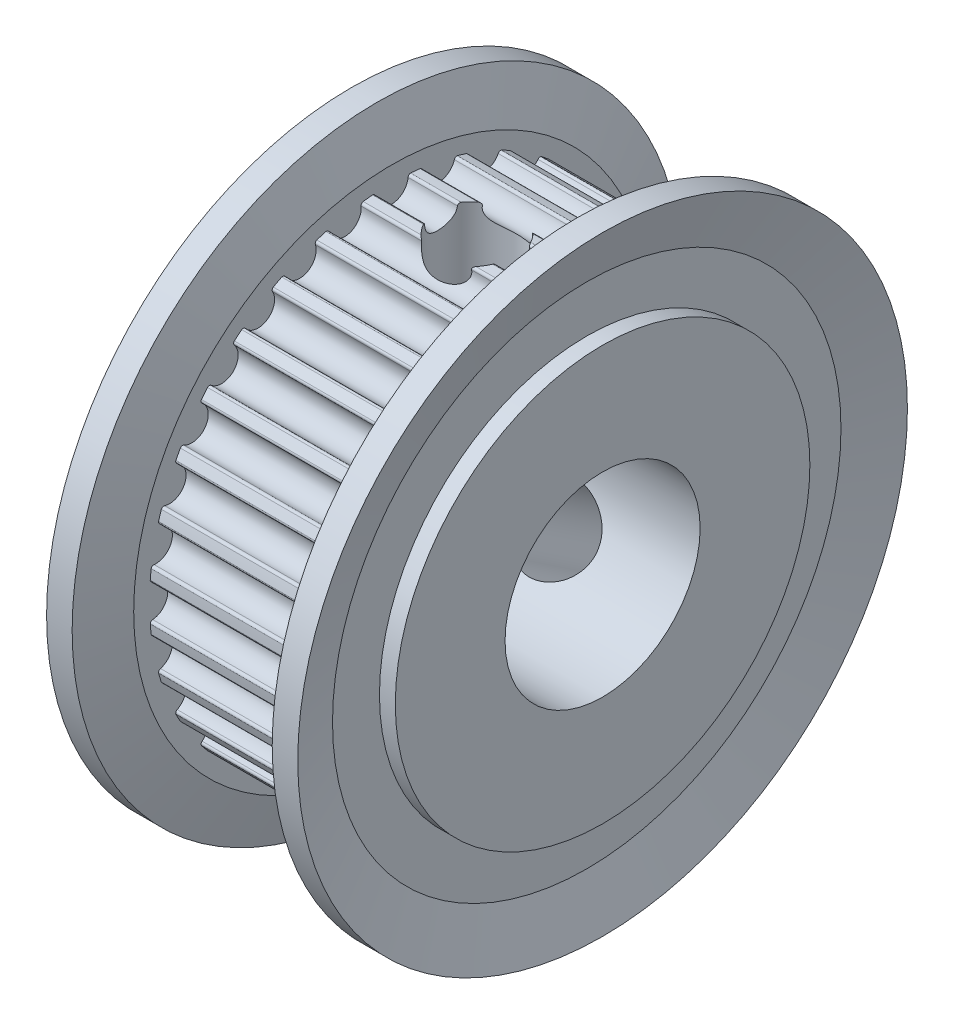
SolidWorks part; units mm, degrees
ref_plane "Front Plane" through (0, 0, 0) normal (0, 0, 1) x (1, 0, 0)
ref_plane "Top Plane" through (0, 0, 0) normal (0, 1, 0) x (1, 0, 0)
ref_plane "Right Plane" through (0, 0, 0) normal (1, 0, 0) x (0, 0, -1)
ref_plane "Plane1" through (0, 0, 0) normal (0, 0, 1) x (1, 0, 0)
sketch "Sketch1" plane through (0, 0, 0) normal (0, 0, 1) x (1, 0, 0)
  line L0 (-5.15, 0) -> (-5.15, 8.5)
  line L1 (-5.15, 8.5) -> (-3.5, 8.5)
  line L2 (-3.5, 8.5) -> (-3.5, 9.93)
  line L3 (-3.5, 9.93) -> (3.5, 9.93)
  line L4 (3.5, 9.93) -> (3.5, 8.5)
  line L5 (3.5, 8.5) -> (5.15, 8.5)
  line L6 (5.15, 8.5) -> (5.15, 0)
  line L7 (5.15, 0) -> (-5.15, 0)
  line L8 (5.15, 0) -> (-5.15, 0) construction
revolve "Revolve1" add sketch "Sketch1" angle 360 about L8
ref_plane "Plane2" through (0, 0, 0) normal (1, 0, 0) x (0, 0, -1)
sketch "Sketch2" plane through (0, 0, 0) normal (1, 0, 0) x (0, 0, -1)
  line L0 (-0.9509, 10.1405) -> (-0.9273, 9.8885)
  line L1 (-0.9273, 9.8885) -> (-0.793, 9.8993)
  line L2 (0.793, 9.8993) -> (0.9273, 9.8885)
  line L3 (0.9273, 9.8885) -> (0.9509, 10.1405)
  arc A0 (-0.793, 9.8993) -> (-0.6724, 9.7974) centre (-0.784, 9.7876) cw
  arc A1 (-0.6724, 9.7974) -> (0.6724, 9.7974) centre (0, 9.856) ccw
  arc A2 (0.6724, 9.7974) -> (0.793, 9.8993) centre (0.784, 9.7876) cw
  arc A3 (0.9509, 10.1405) -> (-0.9509, 10.1405) centre (0, 0) ccw
extrude "Cut-Extrude1" cut sketch "Sketch2" against normal blind 3.5 and the other way blind 3.5
ref_plane "Plane3" through (0, 0, 0) normal (1, 0, 0) x (0, 0, -1)
sketch "Sketch3" plane through (0, 0, 0) normal (1, 0, 0) x (0, 0, -1)
  line L0 (-2.911, 9.7602) -> (-2.8386, 9.5176)
  line L1 (-2.8386, 9.5176) -> (-2.709, 9.5544)
  line L2 (-1.1535, 9.8638) -> (-1.0197, 9.8794)
  line L3 (-1.0197, 9.8794) -> (-1.0457, 10.1312)
  arc A0 (-2.709, 9.5544) -> (-2.5709, 9.4779) centre (-2.6784, 9.4466) cw
  arc A1 (-2.5709, 9.4779) -> (-1.2518, 9.7403) centre (-1.9228, 9.6666) ccw
  arc A2 (-1.2518, 9.7403) -> (-1.1535, 9.8638) centre (-1.1405, 9.7525) cw
  arc A3 (-1.0457, 10.1312) -> (-2.911, 9.7602) centre (0, 0) ccw
extrude "Cut-Extrude2" cut sketch "Sketch3" against normal blind 3.5 and the other way blind 3.5
ref_plane "Plane4" through (0, 0, 0) normal (1, 0, 0) x (0, 0, -1)
sketch "Sketch4" plane through (0, 0, 0) normal (1, 0, 0) x (0, 0, -1)
  line L0 (-4.7591, 9.0047) -> (-4.6409, 8.781)
  line L1 (-4.6409, 8.781) -> (-4.5209, 8.8423)
  line L2 (-3.0557, 9.4492) -> (-2.9275, 9.4907)
  line L3 (-2.9275, 9.4907) -> (-3.0021, 9.7325)
  arc A0 (-4.5209, 8.8423) -> (-4.3706, 8.7943) centre (-4.4699, 8.7426) cw
  arc A1 (-4.3706, 8.7943) -> (-3.128, 9.3089) centre (-3.7717, 9.1058) ccw
  arc A2 (-3.128, 9.3089) -> (-3.0557, 9.4492) centre (-3.0212, 9.3426) cw
  arc A3 (-3.0021, 9.7325) -> (-4.7591, 9.0047) centre (0, 0) ccw
extrude "Cut-Extrude3" cut sketch "Sketch4" against normal blind 3.5 and the other way blind 3.5
ref_plane "Plane5" through (0, 0, 0) normal (1, 0, 0) x (0, 0, -1)
sketch "Sketch5" plane through (0, 0, 0) normal (1, 0, 0) x (0, 0, -1)
  line L0 (-6.4244, 7.9032) -> (-6.2648, 7.7068)
  line L1 (-6.2648, 7.7068) -> (-6.1591, 7.7904)
  line L2 (-4.8404, 8.6715) -> (-4.7228, 8.7372)
  line L3 (-4.7228, 8.7372) -> (-4.8431, 8.9598)
  arc A0 (-6.1591, 7.7904) -> (-6.0023, 7.7726) centre (-6.0896, 7.7026) cw
  arc A1 (-6.0023, 7.7726) -> (-4.884, 8.5198) centre (-5.4757, 8.195) ccw
  arc A2 (-4.884, 8.5198) -> (-4.8404, 8.6715) centre (-4.7858, 8.5737) cw
  arc A3 (-4.8431, 8.9598) -> (-6.4244, 7.9032) centre (0, 0) ccw
extrude "Cut-Extrude4" cut sketch "Sketch5" against normal blind 3.5 and the other way blind 3.5
ref_plane "Plane6" through (0, 0, 0) normal (1, 0, 0) x (0, 0, -1)
sketch "Sketch6" plane through (0, 0, 0) normal (1, 0, 0) x (0, 0, -1)
  line L0 (-7.8428, 6.498) -> (-7.6479, 6.3366)
  line L1 (-7.6479, 6.3366) -> (-7.5606, 6.4391)
  line L2 (-6.4391, 7.5606) -> (-6.3366, 7.6479)
  line L3 (-6.3366, 7.6479) -> (-6.498, 7.8428)
  arc A0 (-7.5606, 6.4391) -> (-7.4033, 6.4523) centre (-7.4753, 6.3665) cw
  arc A1 (-7.4033, 6.4523) -> (-6.4523, 7.4033) centre (-6.9692, 6.9692) ccw
  arc A2 (-6.4523, 7.4033) -> (-6.4391, 7.5606) centre (-6.3665, 7.4753) cw
  arc A3 (-6.498, 7.8428) -> (-7.8428, 6.498) centre (0, 0) ccw
extrude "Cut-Extrude5" cut sketch "Sketch6" against normal blind 3.5 and the other way blind 3.5
ref_plane "Plane7" through (0, 0, 0) normal (1, 0, 0) x (0, 0, -1)
sketch "Sketch7" plane through (0, 0, 0) normal (1, 0, 0) x (0, 0, -1)
  line L0 (-8.9598, 4.8431) -> (-8.7372, 4.7228)
  line L1 (-8.7372, 4.7228) -> (-8.6715, 4.8404)
  line L2 (-7.7904, 6.1591) -> (-7.7068, 6.2648)
  line L3 (-7.7068, 6.2648) -> (-7.9032, 6.4244)
  arc A0 (-8.6715, 4.8404) -> (-8.5198, 4.884) centre (-8.5737, 4.7858) cw
  arc A1 (-8.5198, 4.884) -> (-7.7726, 6.0023) centre (-8.195, 5.4757) ccw
  arc A2 (-7.7726, 6.0023) -> (-7.7904, 6.1591) centre (-7.7026, 6.0896) cw
  arc A3 (-7.9032, 6.4244) -> (-8.9598, 4.8431) centre (0, 0) ccw
extrude "Cut-Extrude6" cut sketch "Sketch7" against normal blind 3.5 and the other way blind 3.5
ref_plane "Plane8" through (0, 0, 0) normal (1, 0, 0) x (0, 0, -1)
sketch "Sketch8" plane through (0, 0, 0) normal (1, 0, 0) x (0, 0, -1)
  line L0 (-9.7325, 3.0021) -> (-9.4907, 2.9275)
  line L1 (-9.4907, 2.9275) -> (-9.4492, 3.0557)
  line L2 (-8.8423, 4.5209) -> (-8.781, 4.6409)
  line L3 (-8.781, 4.6409) -> (-9.0047, 4.7591)
  arc A0 (-9.4492, 3.0557) -> (-9.3089, 3.128) centre (-9.3426, 3.0212) cw
  arc A1 (-9.3089, 3.128) -> (-8.7943, 4.3706) centre (-9.1058, 3.7717) ccw
  arc A2 (-8.7943, 4.3706) -> (-8.8423, 4.5209) centre (-8.7426, 4.4699) cw
  arc A3 (-9.0047, 4.7591) -> (-9.7325, 3.0021) centre (0, 0) ccw
extrude "Cut-Extrude7" cut sketch "Sketch8" against normal blind 3.5 and the other way blind 3.5
ref_plane "Plane9" through (0, 0, 0) normal (1, 0, 0) x (0, 0, -1)
sketch "Sketch9" plane through (0, 0, 0) normal (1, 0, 0) x (0, 0, -1)
  line L0 (-10.1312, 1.0457) -> (-9.8794, 1.0197)
  line L1 (-9.8794, 1.0197) -> (-9.8638, 1.1535)
  line L2 (-9.5544, 2.709) -> (-9.5176, 2.8386)
  line L3 (-9.5176, 2.8386) -> (-9.7602, 2.911)
  arc A0 (-9.8638, 1.1535) -> (-9.7403, 1.2518) centre (-9.7525, 1.1405) cw
  arc A1 (-9.7403, 1.2518) -> (-9.4779, 2.5709) centre (-9.6666, 1.9228) ccw
  arc A2 (-9.4779, 2.5709) -> (-9.5544, 2.709) centre (-9.4466, 2.6784) cw
  arc A3 (-9.7602, 2.911) -> (-10.1312, 1.0457) centre (0, 0) ccw
extrude "Cut-Extrude8" cut sketch "Sketch9" against normal blind 3.5 and the other way blind 3.5
ref_plane "Plane10" through (0, 0, 0) normal (1, 0, 0) x (0, 0, -1)
sketch "Sketch10" plane through (0, 0, 0) normal (1, 0, 0) x (0, 0, -1)
  line L0 (-10.1405, -0.9509) -> (-9.8885, -0.9273)
  line L1 (-9.8885, -0.9273) -> (-9.8993, -0.793)
  line L2 (-9.8993, 0.793) -> (-9.8885, 0.9273)
  line L3 (-9.8885, 0.9273) -> (-10.1405, 0.9509)
  arc A0 (-9.8993, -0.793) -> (-9.7974, -0.6724) centre (-9.7876, -0.784) cw
  arc A1 (-9.7974, -0.6724) -> (-9.7974, 0.6724) centre (-9.856, 0) ccw
  arc A2 (-9.7974, 0.6724) -> (-9.8993, 0.793) centre (-9.7876, 0.784) cw
  arc A3 (-10.1405, 0.9509) -> (-10.1405, -0.9509) centre (0, 0) ccw
extrude "Cut-Extrude9" cut sketch "Sketch10" against normal blind 3.5 and the other way blind 3.5
ref_plane "Plane11" through (0, 0, 0) normal (1, 0, 0) x (0, 0, -1)
sketch "Sketch11" plane through (0, 0, 0) normal (1, 0, 0) x (0, 0, -1)
  line L0 (-9.7602, -2.911) -> (-9.5176, -2.8386)
  line L1 (-9.5176, -2.8386) -> (-9.5544, -2.709)
  line L2 (-9.8638, -1.1535) -> (-9.8794, -1.0197)
  line L3 (-9.8794, -1.0197) -> (-10.1312, -1.0457)
  arc A0 (-9.5544, -2.709) -> (-9.4779, -2.5709) centre (-9.4466, -2.6784) cw
  arc A1 (-9.4779, -2.5709) -> (-9.7403, -1.2518) centre (-9.6666, -1.9228) ccw
  arc A2 (-9.7403, -1.2518) -> (-9.8638, -1.1535) centre (-9.7525, -1.1405) cw
  arc A3 (-10.1312, -1.0457) -> (-9.7602, -2.911) centre (0, 0) ccw
extrude "Cut-Extrude10" cut sketch "Sketch11" against normal blind 3.5 and the other way blind 3.5
ref_plane "Plane12" through (0, 0, 0) normal (1, 0, 0) x (0, 0, -1)
sketch "Sketch12" plane through (0, 0, 0) normal (1, 0, 0) x (0, 0, -1)
  line L0 (-9.0047, -4.7591) -> (-8.781, -4.6409)
  line L1 (-8.781, -4.6409) -> (-8.8423, -4.5209)
  line L2 (-9.4492, -3.0557) -> (-9.4907, -2.9275)
  line L3 (-9.4907, -2.9275) -> (-9.7325, -3.0021)
  arc A0 (-8.8423, -4.5209) -> (-8.7943, -4.3706) centre (-8.7426, -4.4699) cw
  arc A1 (-8.7943, -4.3706) -> (-9.3089, -3.128) centre (-9.1058, -3.7717) ccw
  arc A2 (-9.3089, -3.128) -> (-9.4492, -3.0557) centre (-9.3426, -3.0212) cw
  arc A3 (-9.7325, -3.0021) -> (-9.0047, -4.7591) centre (0, 0) ccw
extrude "Cut-Extrude11" cut sketch "Sketch12" against normal blind 3.5 and the other way blind 3.5
ref_plane "Plane13" through (0, 0, 0) normal (1, 0, 0) x (0, 0, -1)
sketch "Sketch13" plane through (0, 0, 0) normal (1, 0, 0) x (0, 0, -1)
  line L0 (-7.9032, -6.4244) -> (-7.7068, -6.2648)
  line L1 (-7.7068, -6.2648) -> (-7.7904, -6.1591)
  line L2 (-8.6715, -4.8404) -> (-8.7372, -4.7228)
  line L3 (-8.7372, -4.7228) -> (-8.9598, -4.8431)
  arc A0 (-7.7904, -6.1591) -> (-7.7726, -6.0023) centre (-7.7026, -6.0896) cw
  arc A1 (-7.7726, -6.0023) -> (-8.5198, -4.884) centre (-8.195, -5.4757) ccw
  arc A2 (-8.5198, -4.884) -> (-8.6715, -4.8404) centre (-8.5737, -4.7858) cw
  arc A3 (-8.9598, -4.8431) -> (-7.9032, -6.4244) centre (0, 0) ccw
extrude "Cut-Extrude12" cut sketch "Sketch13" against normal blind 3.5 and the other way blind 3.5
ref_plane "Plane14" through (0, 0, 0) normal (1, 0, 0) x (0, 0, -1)
sketch "Sketch14" plane through (0, 0, 0) normal (1, 0, 0) x (0, 0, -1)
  line L0 (-6.498, -7.8428) -> (-6.3366, -7.6479)
  line L1 (-6.3366, -7.6479) -> (-6.4391, -7.5606)
  line L2 (-7.5606, -6.4391) -> (-7.6479, -6.3366)
  line L3 (-7.6479, -6.3366) -> (-7.8428, -6.498)
  arc A0 (-6.4391, -7.5606) -> (-6.4523, -7.4033) centre (-6.3665, -7.4753) cw
  arc A1 (-6.4523, -7.4033) -> (-7.4033, -6.4523) centre (-6.9692, -6.9692) ccw
  arc A2 (-7.4033, -6.4523) -> (-7.5606, -6.4391) centre (-7.4753, -6.3665) cw
  arc A3 (-7.8428, -6.498) -> (-6.498, -7.8428) centre (0, 0) ccw
extrude "Cut-Extrude13" cut sketch "Sketch14" against normal blind 3.5 and the other way blind 3.5
ref_plane "Plane15" through (0, 0, 0) normal (1, 0, 0) x (0, 0, -1)
sketch "Sketch15" plane through (0, 0, 0) normal (1, 0, 0) x (0, 0, -1)
  line L0 (-4.8431, -8.9598) -> (-4.7228, -8.7372)
  line L1 (-4.7228, -8.7372) -> (-4.8404, -8.6715)
  line L2 (-6.1591, -7.7904) -> (-6.2648, -7.7068)
  line L3 (-6.2648, -7.7068) -> (-6.4244, -7.9032)
  arc A0 (-4.8404, -8.6715) -> (-4.884, -8.5198) centre (-4.7858, -8.5737) cw
  arc A1 (-4.884, -8.5198) -> (-6.0023, -7.7726) centre (-5.4757, -8.195) ccw
  arc A2 (-6.0023, -7.7726) -> (-6.1591, -7.7904) centre (-6.0896, -7.7026) cw
  arc A3 (-6.4244, -7.9032) -> (-4.8431, -8.9598) centre (0, 0) ccw
extrude "Cut-Extrude14" cut sketch "Sketch15" against normal blind 3.5 and the other way blind 3.5
ref_plane "Plane16" through (0, 0, 0) normal (1, 0, 0) x (0, 0, -1)
sketch "Sketch16" plane through (0, 0, 0) normal (1, 0, 0) x (0, 0, -1)
  line L0 (-3.0021, -9.7325) -> (-2.9275, -9.4907)
  line L1 (-2.9275, -9.4907) -> (-3.0557, -9.4492)
  line L2 (-4.5209, -8.8423) -> (-4.6409, -8.781)
  line L3 (-4.6409, -8.781) -> (-4.7591, -9.0047)
  arc A0 (-3.0557, -9.4492) -> (-3.128, -9.3089) centre (-3.0212, -9.3426) cw
  arc A1 (-3.128, -9.3089) -> (-4.3706, -8.7943) centre (-3.7717, -9.1058) ccw
  arc A2 (-4.3706, -8.7943) -> (-4.5209, -8.8423) centre (-4.4699, -8.7426) cw
  arc A3 (-4.7591, -9.0047) -> (-3.0021, -9.7325) centre (0, 0) ccw
extrude "Cut-Extrude15" cut sketch "Sketch16" against normal blind 3.5 and the other way blind 3.5
ref_plane "Plane17" through (0, 0, 0) normal (1, 0, 0) x (0, 0, -1)
sketch "Sketch17" plane through (0, 0, 0) normal (1, 0, 0) x (0, 0, -1)
  line L0 (-1.0457, -10.1312) -> (-1.0197, -9.8794)
  line L1 (-1.0197, -9.8794) -> (-1.1535, -9.8638)
  line L2 (-2.709, -9.5544) -> (-2.8386, -9.5176)
  line L3 (-2.8386, -9.5176) -> (-2.911, -9.7602)
  arc A0 (-1.1535, -9.8638) -> (-1.2518, -9.7403) centre (-1.1405, -9.7525) cw
  arc A1 (-1.2518, -9.7403) -> (-2.5709, -9.4779) centre (-1.9228, -9.6666) ccw
  arc A2 (-2.5709, -9.4779) -> (-2.709, -9.5544) centre (-2.6784, -9.4466) cw
  arc A3 (-2.911, -9.7602) -> (-1.0457, -10.1312) centre (0, 0) ccw
extrude "Cut-Extrude16" cut sketch "Sketch17" against normal blind 3.5 and the other way blind 3.5
ref_plane "Plane18" through (0, 0, 0) normal (1, 0, 0) x (0, 0, -1)
sketch "Sketch18" plane through (0, 0, 0) normal (1, 0, 0) x (0, 0, -1)
  line L0 (0.9509, -10.1405) -> (0.9273, -9.8885)
  line L1 (0.9273, -9.8885) -> (0.793, -9.8993)
  line L2 (-0.793, -9.8993) -> (-0.9273, -9.8885)
  line L3 (-0.9273, -9.8885) -> (-0.9509, -10.1405)
  arc A0 (0.793, -9.8993) -> (0.6724, -9.7974) centre (0.784, -9.7876) cw
  arc A1 (0.6724, -9.7974) -> (-0.6724, -9.7974) centre (0, -9.856) ccw
  arc A2 (-0.6724, -9.7974) -> (-0.793, -9.8993) centre (-0.784, -9.7876) cw
  arc A3 (-0.9509, -10.1405) -> (0.9509, -10.1405) centre (0, 0) ccw
extrude "Cut-Extrude17" cut sketch "Sketch18" against normal blind 3.5 and the other way blind 3.5
ref_plane "Plane19" through (0, 0, 0) normal (1, 0, 0) x (0, 0, -1)
sketch "Sketch19" plane through (0, 0, 0) normal (1, 0, 0) x (0, 0, -1)
  line L0 (2.911, -9.7602) -> (2.8386, -9.5176)
  line L1 (2.8386, -9.5176) -> (2.709, -9.5544)
  line L2 (1.1535, -9.8638) -> (1.0197, -9.8794)
  line L3 (1.0197, -9.8794) -> (1.0457, -10.1312)
  arc A0 (2.709, -9.5544) -> (2.5709, -9.4779) centre (2.6784, -9.4466) cw
  arc A1 (2.5709, -9.4779) -> (1.2518, -9.7403) centre (1.9228, -9.6666) ccw
  arc A2 (1.2518, -9.7403) -> (1.1535, -9.8638) centre (1.1405, -9.7525) cw
  arc A3 (1.0457, -10.1312) -> (2.911, -9.7602) centre (0, 0) ccw
extrude "Cut-Extrude18" cut sketch "Sketch19" against normal blind 3.5 and the other way blind 3.5
ref_plane "Plane20" through (0, 0, 0) normal (1, 0, 0) x (0, 0, -1)
sketch "Sketch20" plane through (0, 0, 0) normal (1, 0, 0) x (0, 0, -1)
  line L0 (4.7591, -9.0047) -> (4.6409, -8.781)
  line L1 (4.6409, -8.781) -> (4.5209, -8.8423)
  line L2 (3.0557, -9.4492) -> (2.9275, -9.4907)
  line L3 (2.9275, -9.4907) -> (3.0021, -9.7325)
  arc A0 (4.5209, -8.8423) -> (4.3706, -8.7943) centre (4.4699, -8.7426) cw
  arc A1 (4.3706, -8.7943) -> (3.128, -9.3089) centre (3.7717, -9.1058) ccw
  arc A2 (3.128, -9.3089) -> (3.0557, -9.4492) centre (3.0212, -9.3426) cw
  arc A3 (3.0021, -9.7325) -> (4.7591, -9.0047) centre (0, 0) ccw
extrude "Cut-Extrude19" cut sketch "Sketch20" against normal blind 3.5 and the other way blind 3.5
ref_plane "Plane21" through (0, 0, 0) normal (1, 0, 0) x (0, 0, -1)
sketch "Sketch21" plane through (0, 0, 0) normal (1, 0, 0) x (0, 0, -1)
  line L0 (6.4244, -7.9032) -> (6.2648, -7.7068)
  line L1 (6.2648, -7.7068) -> (6.1591, -7.7904)
  line L2 (4.8404, -8.6715) -> (4.7228, -8.7372)
  line L3 (4.7228, -8.7372) -> (4.8431, -8.9598)
  arc A0 (6.1591, -7.7904) -> (6.0023, -7.7726) centre (6.0896, -7.7026) cw
  arc A1 (6.0023, -7.7726) -> (4.884, -8.5198) centre (5.4757, -8.195) ccw
  arc A2 (4.884, -8.5198) -> (4.8404, -8.6715) centre (4.7858, -8.5737) cw
  arc A3 (4.8431, -8.9598) -> (6.4244, -7.9032) centre (0, 0) ccw
extrude "Cut-Extrude20" cut sketch "Sketch21" against normal blind 3.5 and the other way blind 3.5
ref_plane "Plane22" through (0, 0, 0) normal (1, 0, 0) x (0, 0, -1)
sketch "Sketch22" plane through (0, 0, 0) normal (1, 0, 0) x (0, 0, -1)
  line L0 (7.8428, -6.498) -> (7.6479, -6.3366)
  line L1 (7.6479, -6.3366) -> (7.5606, -6.4391)
  line L2 (6.4391, -7.5606) -> (6.3366, -7.6479)
  line L3 (6.3366, -7.6479) -> (6.498, -7.8428)
  arc A0 (7.5606, -6.4391) -> (7.4033, -6.4523) centre (7.4753, -6.3665) cw
  arc A1 (7.4033, -6.4523) -> (6.4523, -7.4033) centre (6.9692, -6.9692) ccw
  arc A2 (6.4523, -7.4033) -> (6.4391, -7.5606) centre (6.3665, -7.4753) cw
  arc A3 (6.498, -7.8428) -> (7.8428, -6.498) centre (0, 0) ccw
extrude "Cut-Extrude21" cut sketch "Sketch22" against normal blind 3.5 and the other way blind 3.5
ref_plane "Plane23" through (0, 0, 0) normal (1, 0, 0) x (0, 0, -1)
sketch "Sketch23" plane through (0, 0, 0) normal (1, 0, 0) x (0, 0, -1)
  line L0 (8.9598, -4.8431) -> (8.7372, -4.7228)
  line L1 (8.7372, -4.7228) -> (8.6715, -4.8404)
  line L2 (7.7904, -6.1591) -> (7.7068, -6.2648)
  line L3 (7.7068, -6.2648) -> (7.9032, -6.4244)
  arc A0 (8.6715, -4.8404) -> (8.5198, -4.884) centre (8.5737, -4.7858) cw
  arc A1 (8.5198, -4.884) -> (7.7726, -6.0023) centre (8.195, -5.4757) ccw
  arc A2 (7.7726, -6.0023) -> (7.7904, -6.1591) centre (7.7026, -6.0896) cw
  arc A3 (7.9032, -6.4244) -> (8.9598, -4.8431) centre (0, 0) ccw
extrude "Cut-Extrude22" cut sketch "Sketch23" against normal blind 3.5 and the other way blind 3.5
ref_plane "Plane24" through (0, 0, 0) normal (1, 0, 0) x (0, 0, -1)
sketch "Sketch24" plane through (0, 0, 0) normal (1, 0, 0) x (0, 0, -1)
  line L0 (9.7325, -3.0021) -> (9.4907, -2.9275)
  line L1 (9.4907, -2.9275) -> (9.4492, -3.0557)
  line L2 (8.8423, -4.5209) -> (8.781, -4.6409)
  line L3 (8.781, -4.6409) -> (9.0047, -4.7591)
  arc A0 (9.4492, -3.0557) -> (9.3089, -3.128) centre (9.3426, -3.0212) cw
  arc A1 (9.3089, -3.128) -> (8.7943, -4.3706) centre (9.1058, -3.7717) ccw
  arc A2 (8.7943, -4.3706) -> (8.8423, -4.5209) centre (8.7426, -4.4699) cw
  arc A3 (9.0047, -4.7591) -> (9.7325, -3.0021) centre (0, 0) ccw
extrude "Cut-Extrude23" cut sketch "Sketch24" against normal blind 3.5 and the other way blind 3.5
ref_plane "Plane25" through (0, 0, 0) normal (1, 0, 0) x (0, 0, -1)
sketch "Sketch25" plane through (0, 0, 0) normal (1, 0, 0) x (0, 0, -1)
  line L0 (10.1312, -1.0457) -> (9.8794, -1.0197)
  line L1 (9.8794, -1.0197) -> (9.8638, -1.1535)
  line L2 (9.5544, -2.709) -> (9.5176, -2.8386)
  line L3 (9.5176, -2.8386) -> (9.7602, -2.911)
  arc A0 (9.8638, -1.1535) -> (9.7403, -1.2518) centre (9.7525, -1.1405) cw
  arc A1 (9.7403, -1.2518) -> (9.4779, -2.5709) centre (9.6666, -1.9228) ccw
  arc A2 (9.4779, -2.5709) -> (9.5544, -2.709) centre (9.4466, -2.6784) cw
  arc A3 (9.7602, -2.911) -> (10.1312, -1.0457) centre (0, 0) ccw
extrude "Cut-Extrude24" cut sketch "Sketch25" against normal blind 3.5 and the other way blind 3.5
ref_plane "Plane26" through (0, 0, 0) normal (1, 0, 0) x (0, 0, -1)
sketch "Sketch26" plane through (0, 0, 0) normal (1, 0, 0) x (0, 0, -1)
  line L0 (10.1405, 0.9509) -> (9.8885, 0.9273)
  line L1 (9.8885, 0.9273) -> (9.8993, 0.793)
  line L2 (9.8993, -0.793) -> (9.8885, -0.9273)
  line L3 (9.8885, -0.9273) -> (10.1405, -0.9509)
  arc A0 (9.8993, 0.793) -> (9.7974, 0.6724) centre (9.7876, 0.784) cw
  arc A1 (9.7974, 0.6724) -> (9.7974, -0.6724) centre (9.856, 0) ccw
  arc A2 (9.7974, -0.6724) -> (9.8993, -0.793) centre (9.7876, -0.784) cw
  arc A3 (10.1405, -0.9509) -> (10.1405, 0.9509) centre (0, 0) ccw
extrude "Cut-Extrude25" cut sketch "Sketch26" against normal blind 3.5 and the other way blind 3.5
ref_plane "Plane27" through (0, 0, 0) normal (1, 0, 0) x (0, 0, -1)
sketch "Sketch27" plane through (0, 0, 0) normal (1, 0, 0) x (0, 0, -1)
  line L0 (9.7602, 2.911) -> (9.5176, 2.8386)
  line L1 (9.5176, 2.8386) -> (9.5544, 2.709)
  line L2 (9.8638, 1.1535) -> (9.8794, 1.0197)
  line L3 (9.8794, 1.0197) -> (10.1312, 1.0457)
  arc A0 (9.5544, 2.709) -> (9.4779, 2.5709) centre (9.4466, 2.6784) cw
  arc A1 (9.4779, 2.5709) -> (9.7403, 1.2518) centre (9.6666, 1.9228) ccw
  arc A2 (9.7403, 1.2518) -> (9.8638, 1.1535) centre (9.7525, 1.1405) cw
  arc A3 (10.1312, 1.0457) -> (9.7602, 2.911) centre (0, 0) ccw
extrude "Cut-Extrude26" cut sketch "Sketch27" against normal blind 3.5 and the other way blind 3.5
ref_plane "Plane28" through (0, 0, 0) normal (1, 0, 0) x (0, 0, -1)
sketch "Sketch28" plane through (0, 0, 0) normal (1, 0, 0) x (0, 0, -1)
  line L0 (9.0047, 4.7591) -> (8.781, 4.6409)
  line L1 (8.781, 4.6409) -> (8.8423, 4.5209)
  line L2 (9.4492, 3.0557) -> (9.4907, 2.9275)
  line L3 (9.4907, 2.9275) -> (9.7325, 3.0021)
  arc A0 (8.8423, 4.5209) -> (8.7943, 4.3706) centre (8.7426, 4.4699) cw
  arc A1 (8.7943, 4.3706) -> (9.3089, 3.128) centre (9.1058, 3.7717) ccw
  arc A2 (9.3089, 3.128) -> (9.4492, 3.0557) centre (9.3426, 3.0212) cw
  arc A3 (9.7325, 3.0021) -> (9.0047, 4.7591) centre (0, 0) ccw
extrude "Cut-Extrude27" cut sketch "Sketch28" against normal blind 3.5 and the other way blind 3.5
ref_plane "Plane29" through (0, 0, 0) normal (1, 0, 0) x (0, 0, -1)
sketch "Sketch29" plane through (0, 0, 0) normal (1, 0, 0) x (0, 0, -1)
  line L0 (7.9032, 6.4244) -> (7.7068, 6.2648)
  line L1 (7.7068, 6.2648) -> (7.7904, 6.1591)
  line L2 (8.6715, 4.8404) -> (8.7372, 4.7228)
  line L3 (8.7372, 4.7228) -> (8.9598, 4.8431)
  arc A0 (7.7904, 6.1591) -> (7.7726, 6.0023) centre (7.7026, 6.0896) cw
  arc A1 (7.7726, 6.0023) -> (8.5198, 4.884) centre (8.195, 5.4757) ccw
  arc A2 (8.5198, 4.884) -> (8.6715, 4.8404) centre (8.5737, 4.7858) cw
  arc A3 (8.9598, 4.8431) -> (7.9032, 6.4244) centre (0, 0) ccw
extrude "Cut-Extrude28" cut sketch "Sketch29" against normal blind 3.5 and the other way blind 3.5
ref_plane "Plane30" through (0, 0, 0) normal (1, 0, 0) x (0, 0, -1)
sketch "Sketch30" plane through (0, 0, 0) normal (1, 0, 0) x (0, 0, -1)
  line L0 (6.498, 7.8428) -> (6.3366, 7.6479)
  line L1 (6.3366, 7.6479) -> (6.4391, 7.5606)
  line L2 (7.5606, 6.4391) -> (7.6479, 6.3366)
  line L3 (7.6479, 6.3366) -> (7.8428, 6.498)
  arc A0 (6.4391, 7.5606) -> (6.4523, 7.4033) centre (6.3665, 7.4753) cw
  arc A1 (6.4523, 7.4033) -> (7.4033, 6.4523) centre (6.9692, 6.9692) ccw
  arc A2 (7.4033, 6.4523) -> (7.5606, 6.4391) centre (7.4753, 6.3665) cw
  arc A3 (7.8428, 6.498) -> (6.498, 7.8428) centre (0, 0) ccw
extrude "Cut-Extrude29" cut sketch "Sketch30" against normal blind 3.5 and the other way blind 3.5
ref_plane "Plane31" through (0, 0, 0) normal (1, 0, 0) x (0, 0, -1)
sketch "Sketch31" plane through (0, 0, 0) normal (1, 0, 0) x (0, 0, -1)
  line L0 (4.8431, 8.9598) -> (4.7228, 8.7372)
  line L1 (4.7228, 8.7372) -> (4.8404, 8.6715)
  line L2 (6.1591, 7.7904) -> (6.2648, 7.7068)
  line L3 (6.2648, 7.7068) -> (6.4244, 7.9032)
  arc A0 (4.8404, 8.6715) -> (4.884, 8.5198) centre (4.7858, 8.5737) cw
  arc A1 (4.884, 8.5198) -> (6.0023, 7.7726) centre (5.4757, 8.195) ccw
  arc A2 (6.0023, 7.7726) -> (6.1591, 7.7904) centre (6.0896, 7.7026) cw
  arc A3 (6.4244, 7.9032) -> (4.8431, 8.9598) centre (0, 0) ccw
extrude "Cut-Extrude30" cut sketch "Sketch31" against normal blind 3.5 and the other way blind 3.5
ref_plane "Plane32" through (0, 0, 0) normal (1, 0, 0) x (0, 0, -1)
sketch "Sketch32" plane through (0, 0, 0) normal (1, 0, 0) x (0, 0, -1)
  line L0 (3.0021, 9.7325) -> (2.9275, 9.4907)
  line L1 (2.9275, 9.4907) -> (3.0557, 9.4492)
  line L2 (4.5209, 8.8423) -> (4.6409, 8.781)
  line L3 (4.6409, 8.781) -> (4.7591, 9.0047)
  arc A0 (3.0557, 9.4492) -> (3.128, 9.3089) centre (3.0212, 9.3426) cw
  arc A1 (3.128, 9.3089) -> (4.3706, 8.7943) centre (3.7717, 9.1058) ccw
  arc A2 (4.3706, 8.7943) -> (4.5209, 8.8423) centre (4.4699, 8.7426) cw
  arc A3 (4.7591, 9.0047) -> (3.0021, 9.7325) centre (0, 0) ccw
extrude "Cut-Extrude31" cut sketch "Sketch32" against normal blind 3.5 and the other way blind 3.5
ref_plane "Plane33" through (0, 0, 0) normal (1, 0, 0) x (0, 0, -1)
sketch "Sketch33" plane through (0, 0, 0) normal (1, 0, 0) x (0, 0, -1)
  line L0 (1.0457, 10.1312) -> (1.0197, 9.8794)
  line L1 (1.0197, 9.8794) -> (1.1535, 9.8638)
  line L2 (2.709, 9.5544) -> (2.8386, 9.5176)
  line L3 (2.8386, 9.5176) -> (2.911, 9.7602)
  arc A0 (1.1535, 9.8638) -> (1.2518, 9.7403) centre (1.1405, 9.7525) cw
  arc A1 (1.2518, 9.7403) -> (2.5709, 9.4779) centre (1.9228, 9.6666) ccw
  arc A2 (2.5709, 9.4779) -> (2.709, 9.5544) centre (2.6784, 9.4466) cw
  arc A3 (2.911, 9.7602) -> (1.0457, 10.1312) centre (0, 0) ccw
extrude "Cut-Extrude32" cut sketch "Sketch33" against normal blind 3.5 and the other way blind 3.5
ref_plane "Plane34" through (0, 0, 0) normal (0, 0, 1) x (1, 0, 0)
sketch "Sketch34" plane through (0, 0, 0) normal (0, 0, 1) x (1, 0, 0)
  line L0 (3.5, 8.5) -> (4.5, 8.5)
  line L1 (4.5, 8.5) -> (4.5, 10.425)
  line L2 (4.5, 10.425) -> (5.15, 12.5)
  line L3 (5.15, 12.5) -> (4.1021, 12.5)
  line L4 (4.1021, 12.5) -> (3.5, 10.578)
  line L5 (3.5, 10.578) -> (3.5, 8.5)
  line L6 (50, 0) -> (-50, 0) construction
revolve "Revolve2" add sketch "Sketch34" angle 360 about L6
ref_plane "Plane35" through (0, 0, 0) normal (0, 0, 1) x (1, 0, 0)
sketch "Sketch35" plane through (0, 0, 0) normal (0, 0, 1) x (1, 0, 0)
  line L0 (-5.15, 12.5) -> (-4.5, 10.425)
  line L1 (-4.5, 10.425) -> (-4.5, 8.5)
  line L2 (-4.5, 8.5) -> (-3.5, 8.5)
  line L3 (-3.5, 8.5) -> (-3.5, 10.578)
  line L4 (-3.5, 10.578) -> (-4.1021, 12.5)
  line L5 (-4.1021, 12.5) -> (-5.15, 12.5)
  line L6 (50, 0) -> (-50, 0) construction
revolve "Revolve3" add sketch "Sketch35" angle 360 about L6
ref_plane "Plane36" through (0, 0, 0) normal (0, 0, 1) x (1, 0, 0)
sketch "Sketch36" plane through (0, 0, 0) normal (0, 0, 1) x (1, 0, 0)
  line L0 (-5.15, 0) -> (-5.15, 4)
  line L1 (-5.15, 4) -> (5.15, 4)
  line L2 (5.15, 4) -> (5.15, 0)
  line L3 (5.15, 0) -> (-5.15, 0)
  line L4 (5.15, 0) -> (-5.15, 0) construction
revolve "Cut-Revolve1" cut sketch "Sketch36" angle 360 about L4
ref_plane "Plane37" through (0, 0, 0) normal (1, 0, 0) x (0, 0, -1)
sketch "Sketch37" plane through (0, 0, 0) normal (1, 0, 0) x (0, 0, -1)
  line L0 (0, 9.93) -> (1.621, 9.93)
  line L1 (1.621, 9.93) -> (1.621, 0)
  line L2 (1.621, 0) -> (0, 0)
  line L3 (0, 0) -> (0, 9.93)
  line L4 (0, 0) -> (0, 9.93) construction
revolve "Cut-Revolve2" cut sketch "Sketch37" angle 360 about L4
ref_plane "Plane38" through (0, 0, 0) normal (1, 0, 0) x (0, 0, -1)
sketch "Sketch38" plane through (0, 0, 0) normal (1, 0, 0) x (0, 0, -1)
  line L0 (8.2565, -5.5168) -> (7.3559, -6.8646)
  line L1 (7.3559, -6.8646) -> (-0.9006, -1.3478)
  line L2 (-0.9006, -1.3478) -> (0, 0)
  line L3 (0, 0) -> (8.2565, -5.5168)
  line L4 (0, 0) -> (8.2565, -5.5168) construction
revolve "Cut-Revolve3" cut sketch "Sketch38" angle 360 about L4
